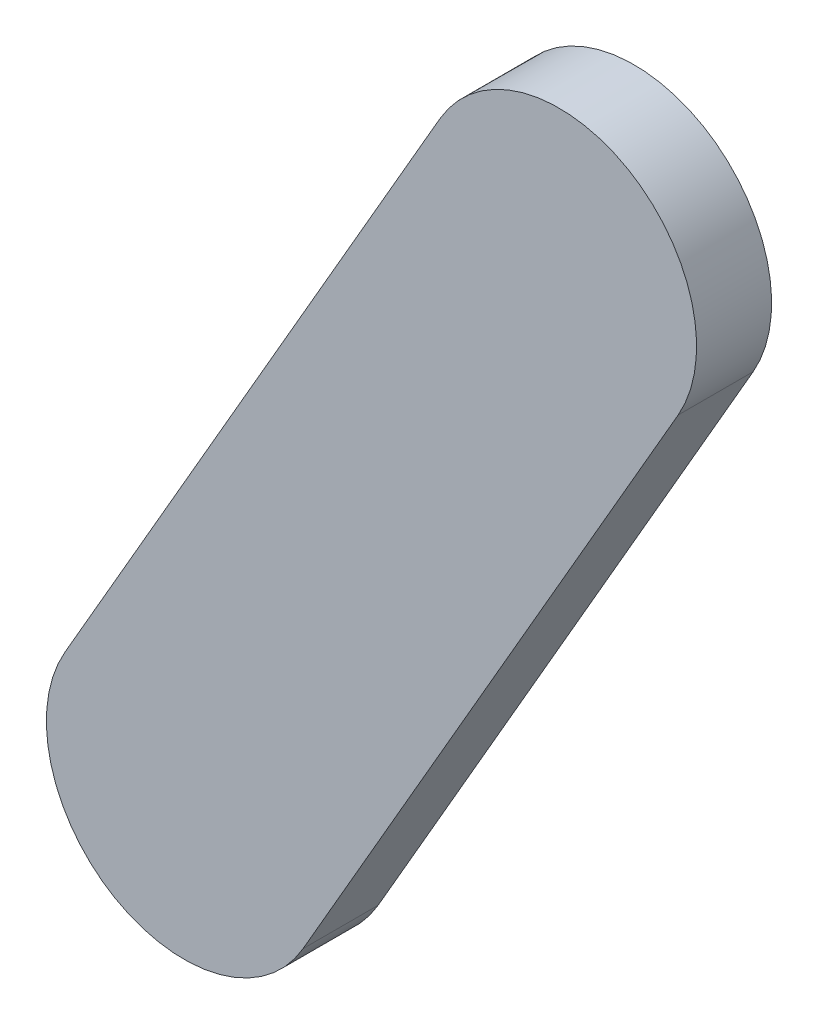
SolidWorks part; units mm, degrees
ref_plane "Front Plane" through (0, 0, 0) normal (0, 0, 1) x (1, 0, 0)
ref_plane "Top Plane" through (0, 0, 0) normal (0, 1, 0) x (1, 0, 0)
ref_plane "Right Plane" through (0, 0, 0) normal (1, 0, 0) x (0, 0, -1)
sketch "Sketch1" plane through (0, 0, 0) normal (0, 0, 1) x (1, 0, 0)
  line L0 (0, 0) -> (15, 25.9808) construction
  line L1 (-4.7631, 2.75) -> (10.2369, 28.7308)
  line L2 (4.7631, -2.75) -> (19.7631, 23.2308)
  line L3 (15, 25.9808) -> (63.4768, 0) construction
  line L4 (17.5981, 30.8284) -> (66.0749, 4.8477)
  line L5 (12.4019, 21.1331) -> (60.8787, -4.8477)
  line L13 (63.4768, 5.5) -> (143.4768, 5.5)
  line L18 (143.4768, 5.5) -> (143.4768, -5.5)
  line L19 (143.4768, -5.5) -> (63.4768, -5.5)
  line L25 (95.8208, 10) -> (135.8208, 10)
  line L26 (95.8208, 10) -> (95.8208, -10)
  line L27 (0, 0) -> (-8.8806, 0) construction
  line L32 (143.4768, 0) -> (57.9768, 0)
  line L33 (63.4768, 5.5) -> (63.4768, -5.5)
  line L34 (71.4768, 5.5) -> (71.4768, -5.5)
  line L35 (95.8208, -10) -> (135.8208, -10)
  line L36 (135.8208, 10) -> (135.8208, -10)
  line L37 (95.8208, 10) -> (135.8208, -10) construction
  line L38 (95.8208, -10) -> (135.8208, 10) construction
  arc A0 (-4.7631, 2.75) -> (4.7631, -2.75) centre (0, 0) ccw
  arc A1 (19.7631, 23.2308) -> (10.2369, 28.7308) centre (15, 25.9808) ccw
  arc A2 (17.5981, 30.8284) -> (12.4019, 21.1331) centre (15, 25.9808) ccw
  arc A3 (60.8787, -4.8477) -> (66.0749, 4.8477) centre (63.4768, 0) ccw
  circle A5 centre (63.4768, 0) radius 5.5
  circle A6 centre (0, 0) radius 10
  point P3 (7.5, 12.9904)
  point P10 (39.2384, 12.9904)
  point P19 (115.8208, 0)
  point P26 (95.8208, 0)
  dimension "D1" = 30
  dimension "D2" = 11
  dimension "D5" = 120
  dimension "D4" = 80
  dimension "D8" = 20
  dimension "D3" = 55
  dimension "D6" = 40
  dimension "D7" = 20
  dimension "D10" = 8
extrude "Boss-Extrude1" add sketch "Sketch1" along normal mid plane 3 contours L1 A1 L2 A0
